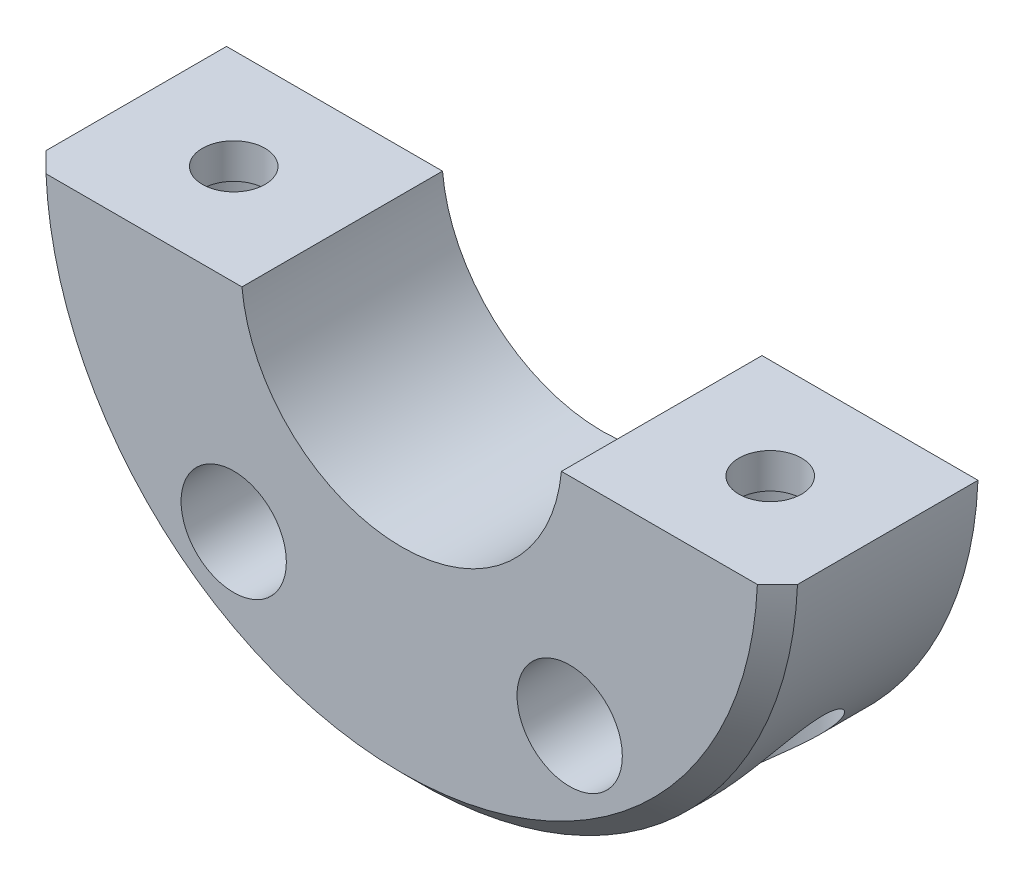
SolidWorks part; units mm, degrees
ref_plane "Front Plane" through (0, 0, 0) normal (0, 0, 1) x (1, 0, 0)
ref_plane "Top Plane" through (0, 0, 0) normal (0, 1, 0) x (1, 0, 0)
ref_plane "Right Plane" through (0, 0, 0) normal (1, 0, 0) x (0, 0, -1)
sketch "Sketch1" plane through (0, 0, 0) normal (0, 0, 1) x (1, 0, 0)
  line L0 (-16, 0) -> (-37.5, 0)
  line L1 (16, 0) -> (37.5, 0)
  arc A0 (-16, 0) -> (16, 0) centre (0, 0) ccw
  arc A1 (-37.5, 0) -> (37.5, 0) centre (0, 0) ccw
  dimension "D1" = 32
  dimension "D2" = 75
extrude "Boss-Extrude1" add sketch "Sketch1" along normal blind 20
sketch "Sketch2" plane through (0, 0, 20) normal (0, 0, 1) x (1, 0, 0)
  circle A0 centre (-16.7519, -23.057) radius 5.25
  circle A1 centre (16.7519, -23.057) radius 5.25
  dimension "D1" = 10.5
  dimension "D2" = 10.5
extrude "Cut-Extrude1" cut sketch "Sketch2" against normal blind 30
sketch "Sketch3" plane through (0, 0, 0) normal (0, 1, 0) x (1, 0, 0)
  line L0 (-37.5, 0) -> (-16, -20) construction
  line L1 (16, 0) -> (37.5, -20) construction
  circle A0 centre (-26.75, -10) radius 3.125
  circle A1 centre (26.75, -10) radius 3.125
  dimension "D1" = 6.25
  dimension "D2" = 6.25
extrude "Cut-Extrude2" cut sketch "Sketch3" against normal blind 30
ref_plane "Plane1" through (0, -38, 0) normal (0, 1, 0) x (1, 0, 0)
sketch "Sketch4" plane through (0, -38, 0) normal (0, 1, 0) x (1, 0, 0)
  circle A0 centre (-26.75, -10) radius 5.25
  circle A1 centre (26.75, -10) radius 5.25
  dimension "D1" = 10.5
  dimension "D2" = 10.5
extrude "Cut-Extrude3" cut sketch "Sketch4" along normal blind 33
chamfer "Chamfer1" distance 2 angle 45 1 edges at (0, -37.5, 20)
sketch "Sketch5" plane through (0, 0, 0) normal (0, 1, 0) x (1, 0, 0)
  line L0 (37.5, -18) -> (37.5, 0) construction
  line L1 (-37.5, 0) -> (37.5, 0)
  line L2 (-37.5, 0) -> (-37.5, -20)
  line L3 (-37.5, -20) -> (37.5, -20)
  line L4 (37.5, 0) -> (37.5, -20)
  line L5 (-16, -20) -> (-35.5, -20) construction
extrude "Cut-Extrude4" cut sketch "Sketch5" against normal blind 1.5
